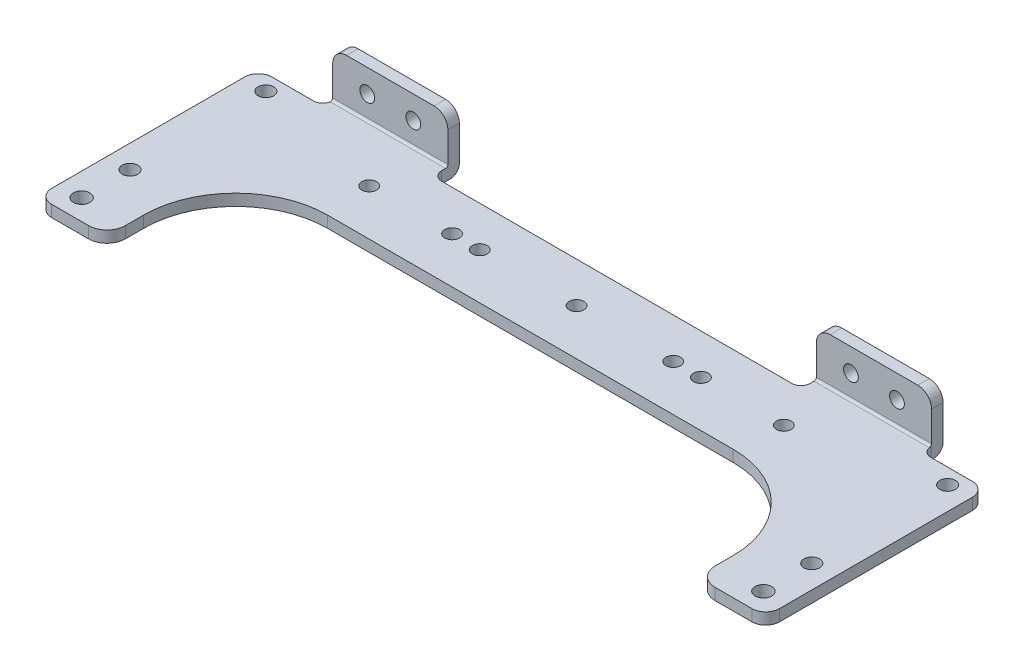
SolidWorks part; units mm, degrees
ref_plane "前视基准面" through (0, 0, 0) normal (0, 0, 1) x (1, 0, 0)
ref_plane "上视基准面" through (0, 0, 0) normal (0, 1, 0) x (1, 0, 0)
ref_plane "右视基准面" through (0, 0, 0) normal (1, 0, 0) x (0, 0, -1)
other "Configuration Table"
sketch "草图1" plane through (0, 0, 0) normal (0, 1, 0) x (1, 0, 0)
  line L1 (-79, -23.9241) -> (79, -23.9241)
  line L2 (-79, -23.9241) -> (-79, 23.9241)
  line L3 (-79, 23.9241) -> (79, 23.9241)
  line L4 (79, -23.9241) -> (79, 23.9241)
  line L5 (-79, -23.9241) -> (79, 23.9241) construction
  line L6 (-79, 23.9241) -> (79, -23.9241) construction
  point P0 (0, 0)
  dimension "D1" = 158
extrude "凸台-拉伸1" add sketch "草图1" along normal blind 2.5
sketch "草图2" plane through (0, 2.5, 0) normal (0, 1, 0) x (1, 0, 0)
  line L0 (-79, -23.9241) -> (-64, -23.9241)
  line L1 (-79, -23.9241) -> (79, -23.9241) construction
  line L2 (79, -23.9241) -> (64, -23.9241)
  line L3 (-64, -23.9241) -> (-64, 4)
  line L4 (64, -23.9241) -> (64, 4)
  line L5 (64, 4) -> (-64, 4)
  line L6 (-64, -23.9241) -> (64, -23.9241)
  line L7 (0, 44.7556) -> (0, -38.056) construction
  line M4 (-79, -23.9241) -> (79, -23.9241)
  dimension "D1" = 128
extrude "切除-拉伸1" cut sketch "草图2" against normal up to next contours L7 L5 L3 M4 | L5 L7 L6 L4
sketch "草图4" plane through (0, 2.5, 0) normal (0, 1, 0) x (1, 0, 0)
  line L0 (-74, -8.9241) -> (-74, 20.5759)
  line L1 (-74, -8.9241) -> (-74, -19.4241)
  line L3 (79, 23.9241) -> (-79, 23.9241) construction
  line L4 (-79, -23.9241) -> (-64, -23.9241) construction
  line L5 (74, 20.5759) -> (74, 23.9241)
  line L6 (74, -8.9241) -> (74, -19.4241)
  line L7 (74, -8.9241) -> (74, 20.5759)
  line L8 (0, 57.2441) -> (0, -49.0894) construction
  circle A6 centre (-74, 20.5759) radius 1.7
  circle A7 centre (-74, -19.4241) radius 1.8
  circle A8 centre (-74, -8.9241) radius 1.7
  circle A9 centre (74, -8.9241) radius 1.7
  circle A10 centre (74, -19.4241) radius 1.8
  circle A11 centre (74, 20.5759) radius 1.7
  point P2 (0, 23.9241)
  dimension "D1" = 148
  dimension "D2" = 4.5
  dimension "D4" = 10.5
  dimension "D5" = 40
extrude "切除-拉伸2" cut sketch "草图4" against normal up to next
sketch "草图5" plane through (0, 2.5, 0) normal (0, 1, 0) x (1, 0, 0)
  circle A0 centre (0, 14) radius 1.6
  circle A1 centre (-45, 14) radius 1.6
  circle A2 centre (45, 14) radius 1.6
extrude "切除-拉伸3" cut sketch "草图5" against normal up to next and the other way through all
fillet "圆角4" radius 3 4 edges at (79, 1.25, -23.9241) (79, 1.25, 23.9241) (-79, 1.25, -23.9241) (-79, 1.25, 23.9241)
fillet "圆角5" radius 4 2 edges at (64, 1.25, 23.9241) (-64, 1.25, 23.9241)
fillet "圆角6" radius 20 2 edges at (-64, 1.25, -4) (64, 1.25, -4)
sketch "草图8" plane through (-79, 0, 0) normal (-1, 0, 0) x (0, 0, 1)
  line L0 (-22.7433, 0) -> (-28.5759, 0)
  line L1 (-28.5759, -29.5) -> (-28.5759, 12.5) construction
  line L2 (-28.5759, 0) -> (-28.5759, 12.5)
  line L3 (-28.5759, 12.5) -> (-26.0759, 12.5)
  line L4 (-26.0759, 12.5) -> (-26.0759, 2.5)
  line L5 (-26.0759, 2.5) -> (-22.7433, 2.5)
  line L6 (-22.7433, 2.5) -> (-22.7433, 0)
  line L8 (-20.9241, 2.5) -> (20.9241, 2.5) construction
  dimension "D1" = 2.5
extrude "凸台-拉伸2" add sketch "草图8" against normal mid plane 130 from offset 79 offset against normal yes
sketch "草图9" plane through (-79, 0, 0) normal (-1, 0, 0) x (0, 0, 1)
  line L6 (-28.5759, 0) -> (-22.7433, 0)
  line L7 (-28.5759, 12.5) -> (-28.5759, 0)
  line L8 (-26.0759, 12.5) -> (-28.5759, 12.5)
  line L9 (-26.0759, 2.5) -> (-26.0759, 12.5)
  line L10 (-22.7433, 2.5) -> (-26.0759, 2.5)
  line L11 (-22.7433, 0) -> (-22.7433, 2.5)
  line L12 (-28.5759, 0) -> (-22.7433, 0)
  line L13 (-28.5759, 12.5) -> (-28.5759, 0)
  line L14 (-26.0759, 12.5) -> (-28.5759, 12.5)
  line L15 (-26.0759, 2.5) -> (-26.0759, 12.5)
  line L16 (-22.7433, 2.5) -> (-26.0759, 2.5)
  line L17 (-22.7433, 0) -> (-22.7433, 2.5)
  dimension "D1" = 0
extrude "切除-拉伸4" cut sketch "草图9" against normal mid plane 80 from offset 79 offset against normal yes
fillet "圆角7" radius 0.5 2 edges at (52.5, 2.5, -26.0759) (-52.5, 2.5, -26.0759)
fillet "圆角8" radius 2 2 edges at (-52.5, 0, -28.5759) (52.5, 0, -28.5759)
fillet "圆角9" radius 3 4 edges at (65, 12.5, -27.3259) (40, 12.5, -27.3259) (-40, 12.5, -27.3259) (-65, 12.5, -27.3259)
fillet "圆角10" radius 2 4 edges at (-65, 1.25, -23.9241) (-40, 1.25, -22.7433) (65, 1.25, -23.9241) (40, 1.25, -22.7433)
sketch "草图10" plane through (0, 0, -26.0759) normal (0, 0, 1) x (1, 0, 0)
  line L0 (0, 22.2809) -> (0, -18.0443) construction
  line L1 (-57.5, 7.5) -> (-47.5, 7.5) construction
  line L2 (-65, 3) -> (-65, 9.5) construction
  line L5 (-43, 12.5) -> (-62, 12.5) construction
  line L6 (-44, 2.5) -> (-64, 2.5) construction
  line L7 (57.5, 7.5) -> (47.5, 7.5) construction
  circle A0 centre (-57.5, 7.5) radius 1.6
  circle A1 centre (-47.5, 7.5) radius 1.6
  circle A2 centre (47.5, 7.5) radius 1.6
  circle A3 centre (57.5, 7.5) radius 1.6
  dimension "D1" = 3.2
  dimension "D2" = 3.2
  dimension "D3" = 7.5
  dimension "D4" = 10
extrude "切除-拉伸5" cut sketch "草图10" against normal through all
sketch "草图11" plane through (0, 2.5, 0) normal (0, 1, 0) x (1, 0, 0)
  line L0 (0, 34.0066) -> (0, -11.4815) construction
  circle A0 centre (-27, 14) radius 1.6
  circle A1 centre (-21, 14) radius 1.6
  circle A2 centre (21, 14) radius 1.6
  circle A3 centre (27, 14) radius 1.6
  point P7 (0, 0)
  point P9 (-45, 14)
  dimension "D1" = 3.2
  dimension "D2" = 3.2
  dimension "D3" = 42
  dimension "D4" = 54
extrude "切除-拉伸6" cut sketch "草图11" against normal through all
